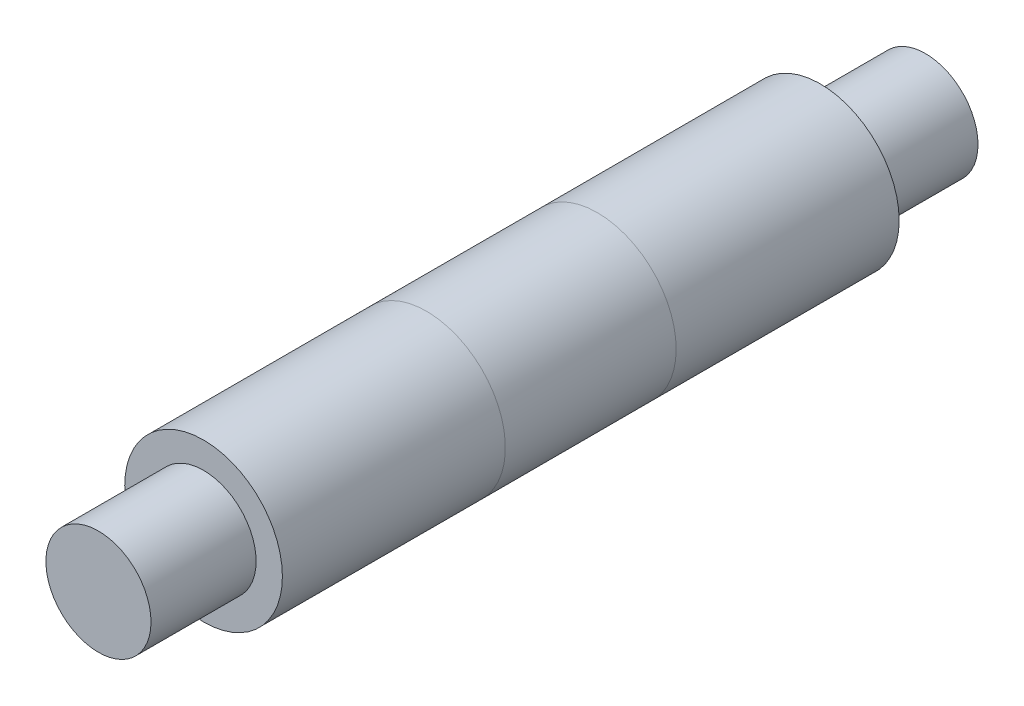
SolidWorks part; units mm, degrees
material "Chrome Stainless Steel"
ref_plane "Plane1" through (0, 0, 0) normal (0, 0, 1) x (1, 0, 0)
ref_plane "Plane2" through (0, 0, 0) normal (0, 1, 0) x (1, 0, 0)
ref_plane "Plane3" through (0, 0, 0) normal (1, 0, 0) x (0, 0, -1)
other "Configuration Table"
sketch "Sketch1" plane through (0, 0, 0) normal (0, 0, 1) x (1, 0, 0)
  circle A0 centre (0, 0) radius 19.05
  dimension "D1" = 38.1
extrude "Center" add sketch "Sketch1" along normal mid plane 149.0472
sketch "Sketch2" plane through (0, 0, 74.5236) normal (0, 0, 1) x (1, 0, 0)
  circle A0 centre (0, 0) radius 12.7
  dimension "D1" = 25.4
extrude "End" add sketch "Sketch2" along normal blind 25.4
mirror "Mirror1" about plane through (0, 0, 0) normal (0, 0, 1) of "End"
sketch "Sketch3" plane through (0, 0, 0) normal (0, 1, 0) x (1, 0, 0)
  line L1 (-38.1, -20.6375) -> (38.1, -20.6375)
  line L2 (-38.1, -20.6375) -> (-38.1, 20.6375)
  line L3 (-38.1, 20.6375) -> (38.1, 20.6375)
  line L4 (38.1, -20.6375) -> (38.1, 20.6375)
  point P4 (0, -20.6375)
  point P5 (38.1, 0)
split line "Split Line1"
